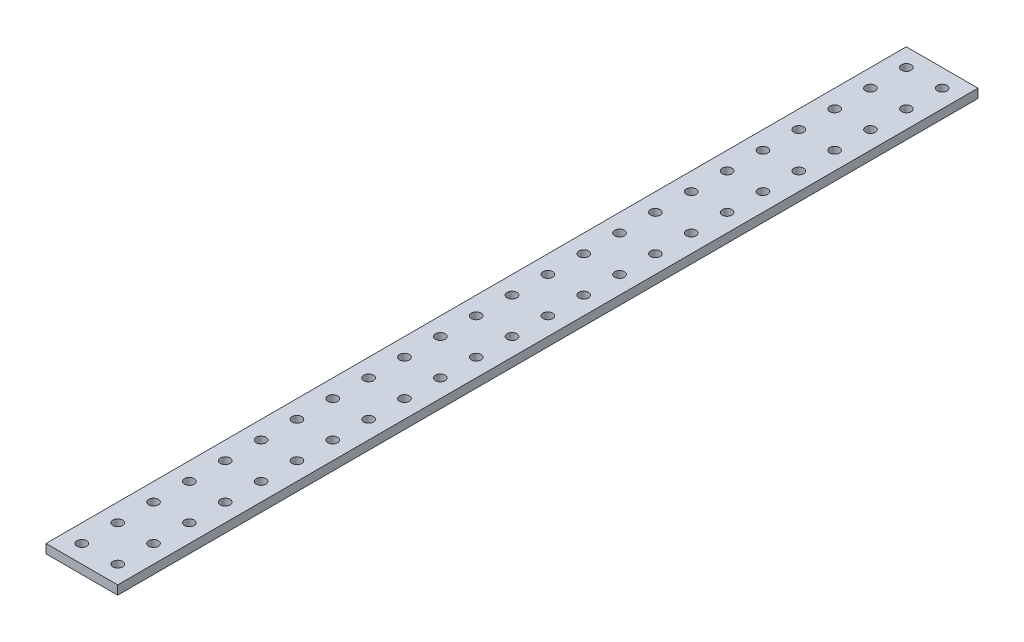
SolidWorks part; units mm, degrees
ref_plane "Front Plane" through (0, 0, 0) normal (0, 0, 1) x (1, 0, 0)
ref_plane "Top Plane" through (0, 0, 0) normal (0, 1, 0) x (1, 0, 0)
ref_plane "Right Plane" through (0, 0, 0) normal (1, 0, 0) x (0, 0, -1)
sketch "Sketch1" plane through (0, 0, 0) normal (0, 1, 0) x (1, 0, 0)
  line L1 (-25.4, -304.8) -> (25.4, -304.8)
  line L2 (-25.4, -304.8) -> (-25.4, 304.8)
  line L3 (-25.4, 304.8) -> (25.4, 304.8)
  line L4 (25.4, -304.8) -> (25.4, 304.8)
  line L5 (-25.4, -304.8) -> (25.4, 304.8) construction
  line L6 (-25.4, 304.8) -> (25.4, -304.8) construction
  circle A0 centre (-12.7, 292.1) radius 3.429
  circle A1 centre (12.7, 292.1) radius 3.429
  circle A2 centre (12.7, 266.7) radius 3.429
  circle A3 centre (12.7, 241.3) radius 3.429
  circle A4 centre (12.7, 215.9) radius 3.429
  circle A5 centre (12.7, 190.5) radius 3.429
  circle A6 centre (12.7, 165.1) radius 3.429
  circle A7 centre (12.7, 139.7) radius 3.429
  circle A8 centre (12.7, 114.3) radius 3.429
  circle A9 centre (12.7, 88.9) radius 3.429
  circle A10 centre (12.7, 63.5) radius 3.429
  circle A11 centre (12.7, 38.1) radius 3.429
  circle A12 centre (12.7, 12.7) radius 3.429
  circle A13 centre (12.7, -12.7) radius 3.429
  circle A14 centre (12.7, -38.1) radius 3.429
  circle A15 centre (12.7, -63.5) radius 3.429
  circle A16 centre (12.7, -88.9) radius 3.429
  circle A17 centre (12.7, -114.3) radius 3.429
  circle A18 centre (12.7, -139.7) radius 3.429
  circle A19 centre (12.7, -165.1) radius 3.429
  circle A20 centre (12.7, -190.5) radius 3.429
  circle A21 centre (12.7, -215.9) radius 3.429
  circle A22 centre (12.7, -241.3) radius 3.429
  circle A23 centre (12.7, -266.7) radius 3.429
  circle A24 centre (12.7, -292.1) radius 3.429
  circle A25 centre (-12.7, 266.7) radius 3.429
  circle A26 centre (-12.7, 241.3) radius 3.429
  circle A27 centre (-12.7, 215.9) radius 3.429
  circle A28 centre (-12.7, 190.5) radius 3.429
  circle A29 centre (-12.7, 165.1) radius 3.429
  circle A30 centre (-12.7, 139.7) radius 3.429
  circle A31 centre (-12.7, 114.3) radius 3.429
  circle A32 centre (-12.7, 88.9) radius 3.429
  circle A33 centre (-12.7, 63.5) radius 3.429
  circle A34 centre (-12.7, 38.1) radius 3.429
  circle A35 centre (-12.7, 12.7) radius 3.429
  circle A36 centre (-12.7, -12.7) radius 3.429
  circle A37 centre (-12.7, -38.1) radius 3.429
  circle A38 centre (-12.7, -63.5) radius 3.429
  circle A39 centre (-12.7, -88.9) radius 3.429
  circle A40 centre (-12.7, -114.3) radius 3.429
  circle A41 centre (-12.7, -139.7) radius 3.429
  circle A42 centre (-12.7, -165.1) radius 3.429
  circle A43 centre (-12.7, -190.5) radius 3.429
  circle A44 centre (-12.7, -215.9) radius 3.429
  circle A45 centre (-12.7, -241.3) radius 3.429
  circle A46 centre (-12.7, -266.7) radius 3.429
  circle A47 centre (-12.7, -292.1) radius 3.429
  point P0 (0, 0)
  dimension "D3" = 6.858
  dimension "D1" = 50.8
  dimension "D2" = 609.6
  dimension "D4" = 12.7
  dimension "D5" = 12.7
  dimension "D6" = 2
  dimension "D7" = 24
extrude "Boss-Extrude1" add sketch "Sketch1" along normal blind 6.35
